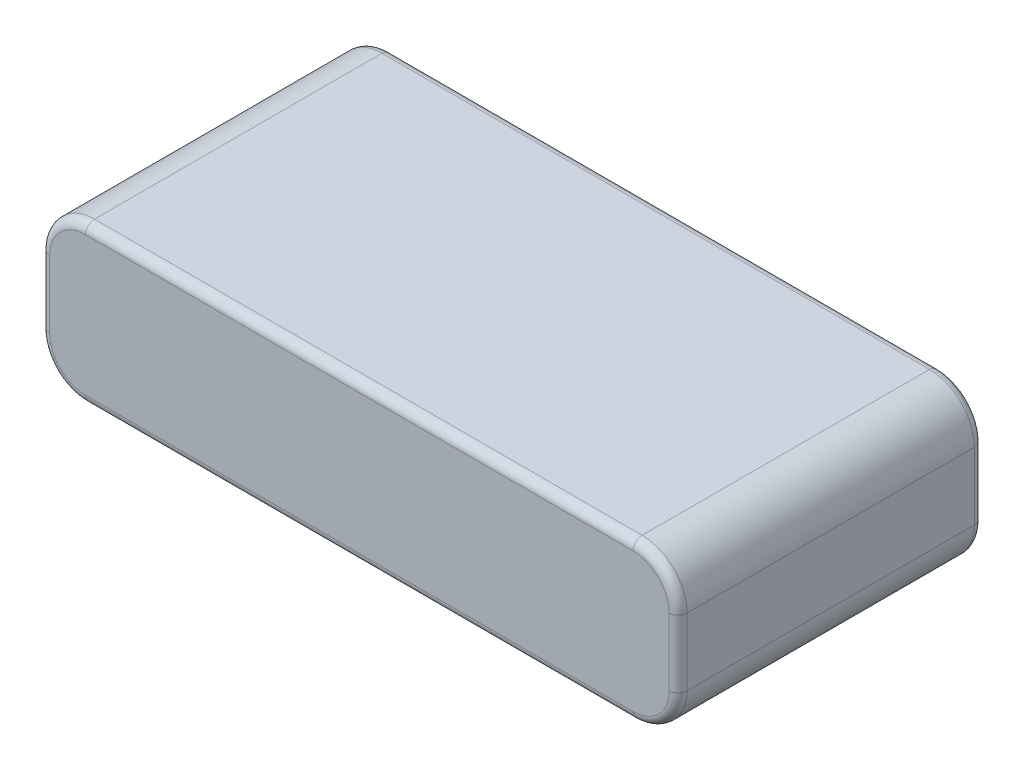
SolidWorks part; units mm, degrees
ref_plane "Front Plane" through (0, 0, 0) normal (0, 0, 1) x (1, 0, 0)
ref_plane "Top Plane" through (0, 0, 0) normal (0, 1, 0) x (1, 0, 0)
ref_plane "Right Plane" through (0, 0, 0) normal (1, 0, 0) x (0, 0, -1)
sketch "Sketch1" plane through (0, 0, 0) normal (0, 1, 0) x (1, 0, 0)
  line L1 (35.5, -17) -> (-35.5, -17)
  line L2 (35.5, -17) -> (35.5, 17)
  line L3 (35.5, 17) -> (-35.5, 17)
  line L4 (-35.5, -17) -> (-35.5, 17)
  line L5 (35.5, -17) -> (-35.5, 17) construction
  line L6 (35.5, 17) -> (-35.5, -17) construction
  point P0 (0, 0)
  dimension "D1" = 71
  dimension "D2" = 34
extrude "Boss-Extrude1" add sketch "Sketch1" along normal blind 17.5
fillet "Fillet1" radius 5 4 edges at (-35.5, 0, 0) (35.5, 0, 0) (35.5, 17.5, 0) (-35.5, 17.5, 0)
fillet "Fillet2" radius 1 16 edges at (34.0355, 1.4645, -17) (35.5, 8.75, -17) (34.0355, 16.0355, -17) (0, 17.5, -17) (-34.0355, 16.0355, -17) (-35.5, 8.75, -17) (-34.0355, 1.4645, -17) (0, 0, -17) (-34.0355, 16.0355, 17) (0, 17.5, 17) (34.0355, 16.0355, 17) (35.5, 8.75, 17) (34.0355, 1.4645, 17) (0, 0, 17) (-34.0355, 1.4645, 17) (-35.5, 8.75, 17)
